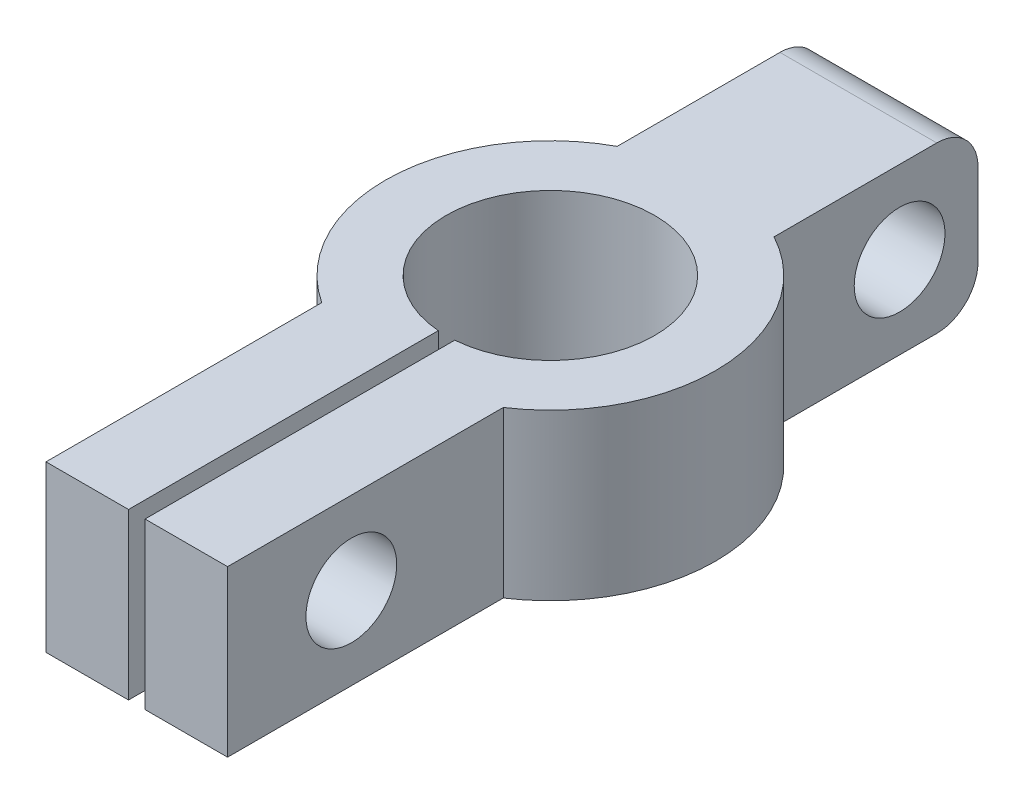
SolidWorks part; units mm, degrees
ref_plane "前视基准面" through (0, 0, 0) normal (0, 0, 1) x (1, 0, 0)
ref_plane "上视基准面" through (0, 0, 0) normal (0, 1, 0) x (1, 0, 0)
ref_plane "右视基准面" through (0, 0, 0) normal (1, 0, 0) x (0, 0, -1)
other "Configuration Table"
sketch "草图1" plane through (0, 0, 0) normal (0, 1, 0) x (1, 0, 0)
  line L0 (-6.6571, 7.5514) -> (-6.6571, 5.5514)
  line L1 (-4.2571, 9.4691) -> (-4.2571, 11.0581)
  line L6 (-2.2571, 10.2345) -> (-2.2571, 7.5514)
  line L8 (-4.2571, 7.5514) -> (-4.2571, 9.4691)
  line L9 (-2.5571, 18.9517) -> (-6.3571, 18.9517) construction
  line L10 (-4.6571, 9.4691) -> (-4.6571, 11.0581)
  line L12 (-6.6571, 10.2345) -> (-6.6571, 7.5514)
  line L14 (-4.6571, 7.5514) -> (-4.6571, 9.4691)
  line L15 (-6.3571, 21.5393) -> (-6.3571, 17.0951)
  line L17 (-2.5571, 17.0951) -> (-2.5571, 21.5393)
  line L18 (-6.6571, 5.5514) -> (-6.6571, 4.5514)
  line L19 (-4.6571, 5.5514) -> (-4.6571, 7.5514)
  line L20 (-4.2571, 7.5514) -> (-4.2571, 5.5514)
  line L22 (-2.2571, 5.5514) -> (-2.2571, 7.5514)
  line L23 (-4.6571, 4.5514) -> (-4.6571, 5.5514)
  line L24 (-4.2571, 5.5514) -> (-4.2571, 4.5514)
  line L26 (-2.2571, 5.5514) -> (-2.2571, 4.5514)
  line L27 (-6.3571, 21.5393) -> (-6.3571, 22.0393)
  line L28 (-6.3571, 22.0393) -> (-2.5571, 22.0393)
  line L29 (-2.5571, 22.0393) -> (-2.5571, 21.5393)
  line L30 (-6.6571, 4.5514) -> (-6.6571, 3.5514)
  line L31 (-6.6571, 3.5514) -> (-4.6571, 3.5514)
  line L32 (-4.6571, 3.5514) -> (-4.6571, 4.5514)
  line L33 (-4.2571, 4.5514) -> (-4.2571, 3.5514)
  line L34 (-4.2571, 3.5514) -> (-2.2571, 3.5514)
  line L35 (-2.2571, 3.5514) -> (-2.2571, 4.5514)
  arc A0 (-4.2571, 11.0581) -> (-4.6571, 11.0581) centre (-4.4571, 13.5752) ccw
  arc A1 (-2.2571, 10.2345) -> (-2.4571, 17.0393) centre (-4.4571, 13.5752) ccw
  arc A2 (-6.4571, 17.0393) -> (-6.6571, 10.2345) centre (-4.4571, 13.5752) ccw
  arc A3 (-6.3571, 17.0951) -> (-6.6571, 10.2345) centre (-4.4571, 13.5752) ccw
  arc A4 (-2.2571, 10.2345) -> (-2.5571, 17.0951) centre (-4.4571, 13.5752) ccw
extrude "凸台-拉伸1" add sketch "草图1" along normal blind 4
sketch "草图2" plane through (-2.4571, 0, 0) normal (1, 0, 0) x (0, 0, -1)
  line L0 (21.5393, 2) -> (20.8393, 2) construction
  line L1 (21.5393, 4) -> (21.5393, 0) construction
  line L2 (20.8393, 2) -> (19.4393, 2) construction
  circle A1 centre (20.1393, 2) radius 1.1
extrude "切除-拉伸1" cut sketch "草图2" against normal blind 4
sketch "草图3" plane through (-6.6571, 0, 0) normal (-1, 0, 0) x (0, 0, 1)
  line L0 (-5.5514, 2) -> (-7.5514, 2) construction
  line L1 (-5.5514, 4) -> (-5.5514, 0) construction
  circle A0 centre (-6.5514, 2) radius 1.1
extrude "切除-拉伸2" cut sketch "草图3" against normal blind 5
fillet "圆角3" radius 1 2 edges at (-4.4571, 0, -22.0393) (-4.4571, 4, -22.0393)
